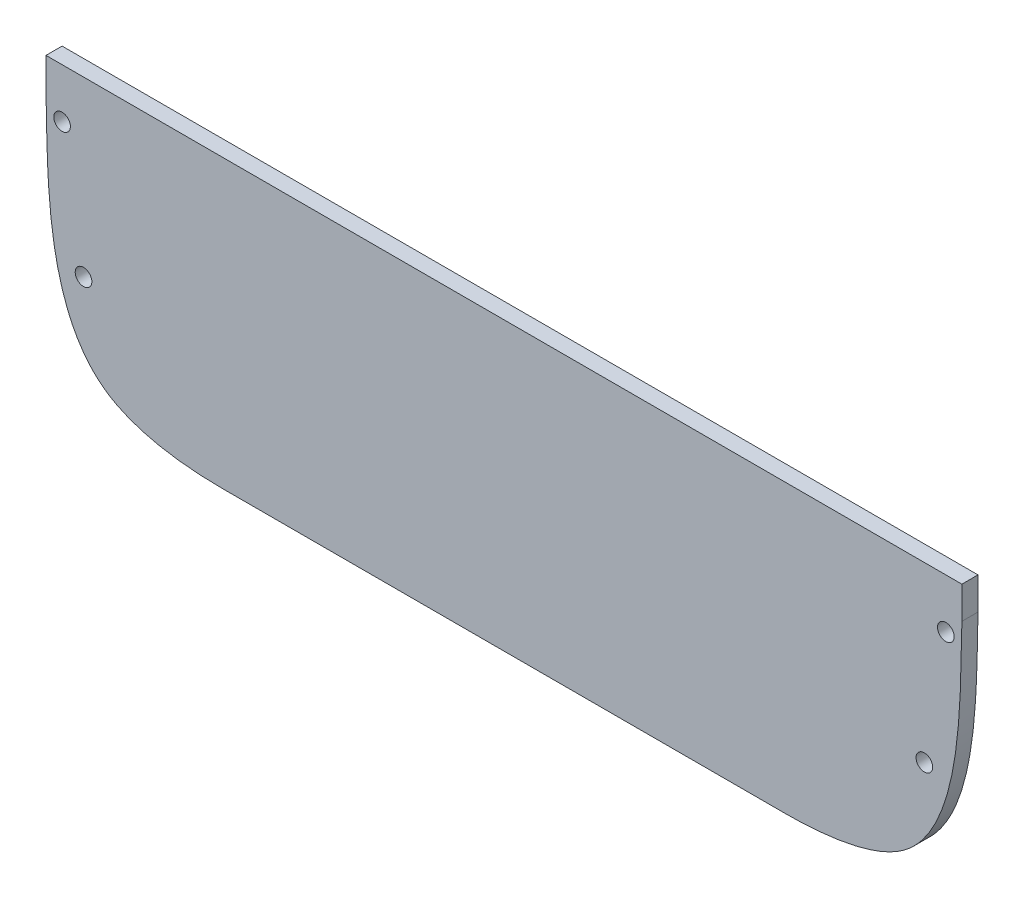
SolidWorks part; units mm, degrees
ref_plane "Front Plane" through (0, 0, 0) normal (0, 0, 1) x (1, 0, 0)
ref_plane "Top Plane" through (0, 0, 0) normal (0, 1, 0) x (1, 0, 0)
ref_plane "Right Plane" through (0, 0, 0) normal (1, 0, 0) x (0, 0, -1)
sketch "Sketch2" plane through (0, 0, 0) normal (0, 0, 1) x (1, 0, 0)
  line L1 (100, -56) -> (-105, -56)
  line L3 (100, -56) -> (105, -56)
  line L4 (0, -58.85) -> (0, 58.85) construction
  line L10 (-170.7701, 51) -> (-170.7701, 39.0001)
  line L12 (-158.7882, 39.9555) -> (-159.0055, 39.9381)
  line L14 (159.0055, 51) -> (-170.7701, 51)
  line L23 (159.0055, 39) -> (158.7658, 39)
  line L25 (170.7701, 39.0001) -> (170.7701, 51)
  line L26 (170.7701, 51) -> (159.0055, 51)
  circle A1 centre (164.7701, 32.5545) radius 3.1
  circle A2 centre (-156.7701, -13.5659) radius 3.1
  circle A4 centre (-164.7701, 32.5545) radius 3.1
  circle A5 centre (156.7701, -13.5659) radius 3.1
  spline S1 degree 3 poles (-170.7701, 39.0002) (-170.7553, 38.4577) (-170.7068, 36.5379) (-170.6373, 33.123) (-170.5261, 27.1841) (-170.3434, 19.367) (-169.8895, 9.6087) (-169.0392, -0.2668) (-167.1706, -13.2343) (-163.8919, -25.3514) (-158.7192, -35.5362) (-153.789, -41.9964) (-147.741, -47.0906) (-140.116, -50.8649) (-131.3295, -53.4958) (-123.6228, -54.8308) (-117.5463, -55.4886) (-113.1121, -55.8039) (-109.5936, -55.9421) (-106.9059, -55.9924) (-105.642, -56) (-105, -56) knots 0.050003 0.050003 0.050003 0.050003 0.0625 0.09375 0.125 0.1875 0.25 0.3125 0.375 0.5 0.5625 0.625 0.6875 0.75 0.8125 0.875 0.90625 0.9375 0.96875 0.984375 1 1 1 1
  spline S4 degree 3 poles (-170.7701, 39.0001) (-170.7553, 38.4575) (-170.7068, 36.5377) (-170.6373, 33.1227) (-170.5683, 29.4358) (-170.5206, 27.1759) (-170.504, 26.4341) knots 0.050001 0.050001 0.050001 0.050001 0.0625 0.09375 0.125 0.140101 0.140101 0.140101 0.140101
  spline S7 degree 3 poles (105, -56) (105.642, -56) (106.9059, -55.9924) (109.5936, -55.9421) (113.1121, -55.8039) (117.5463, -55.4886) (123.6228, -54.8308) (131.3295, -53.4958) (140.116, -50.8649) (147.741, -47.0906) (153.789, -41.9964) (158.7192, -35.5362) (163.8919, -25.3514) (167.1706, -13.2343) (169.0392, -0.2668) (169.8895, 9.6087) (170.3434, 19.367) (170.5261, 27.1841) (170.6373, 33.123) (170.7068, 36.5379) (170.7553, 38.4577) (170.7701, 39.0002) knots 0 0 0 0 0.015625 0.03125 0.0625 0.09375 0.125 0.1875 0.25 0.3125 0.375 0.4375 0.5 0.625 0.6875 0.75 0.8125 0.875 0.90625 0.9375 0.949997 0.949997 0.949997 0.949997
  spline S11 degree 3 poles (170.504, 26.4341) (170.5206, 27.1759) (170.5683, 29.4358) (170.6373, 33.1227) (170.7068, 36.5377) (170.7553, 38.4575) (170.7701, 39.0001) knots 0.859899 0.859899 0.859899 0.859899 0.875 0.90625 0.9375 0.949999 0.949999 0.949999 0.949999
  dimension "D4" = 14
extrude "Boss-Extrude2" add sketch "Sketch2" along normal blind 6
